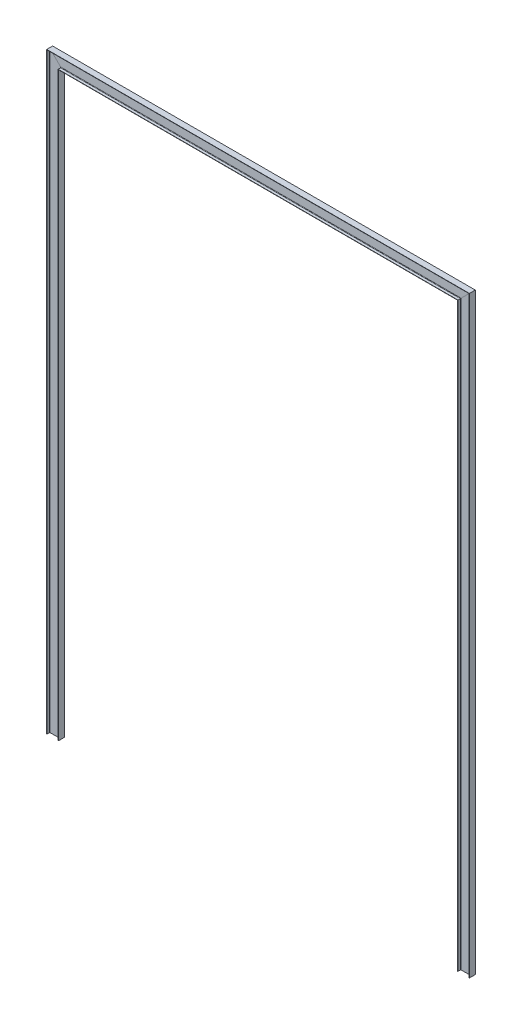
SolidWorks part; units mm, degrees
material "ASTM A36 Steel"
ref_plane "Front Plane" through (0, 0, 0) normal (0, 0, 1) x (1, 0, 0)
ref_plane "Top Plane" through (0, 0, 0) normal (0, 1, 0) x (1, 0, 0)
ref_plane "Right Plane" through (0, 0, 0) normal (1, 0, 0) x (0, 0, -1)
sketch "Sketch1" plane through (0, 0, 0) normal (0, 0, 1) x (1, 0, 0)
  line L0 (0, 0) -> (0, 10000)
  line L1 (0, 10000) -> (7000, 10000)
  line L2 (7000, 10000) -> (7000, 0)
  dimension "D1" = 10000
  dimension "D2" = 7000
other "W section W8X10(1)"
ref_plane "Plane1" through (0, 0, 0) normal (0, 1, 0) x (0, 0, 1)
sketch "Sketch11" plane through (0, 0, 0) normal (0, 1, 0) x (0, 0, 1)
  line L0 (-50.038, -100.203) -> (-50.038, -94.996)
  line L1 (-50.038, -94.996) -> (-9.779, -94.996)
  line L2 (-2.159, -87.376) -> (-2.159, 87.376)
  line L3 (-9.779, 94.996) -> (-50.038, 94.996)
  line L4 (-50.038, 94.996) -> (-50.038, 100.203)
  line L5 (-50.038, 100.203) -> (50.038, 100.203)
  line L6 (50.038, 100.203) -> (50.038, 94.996)
  line L7 (50.038, 94.996) -> (9.779, 94.996)
  line L8 (2.159, 87.376) -> (2.159, -87.376)
  line L9 (9.779, -94.996) -> (50.038, -94.996)
  line L10 (50.038, -94.996) -> (50.038, -100.203)
  line L11 (50.038, -100.203) -> (-50.038, -100.203)
  line L12 (0, 0) -> (0, 100.203) construction
  line L13 (-2.159, 0) -> (2.159, 0) construction
  arc A0 (-9.779, -94.996) -> (-2.159, -87.376) centre (-9.779, -87.376) ccw
  arc A1 (-2.159, 87.376) -> (-9.779, 94.996) centre (-9.779, 87.376) ccw
  arc A2 (9.779, 94.996) -> (2.159, 87.376) centre (9.779, 87.376) ccw
  arc A3 (2.159, -87.376) -> (9.779, -94.996) centre (9.779, -87.376) ccw
  point P23 (-50.038, 0)
  point P26 (0, -100.203)
  point P27 (50.038, 0)
  point P28 (0, 0)
  dimension "Ri" = 7.62
  dimension "D1" = 2.159
  dimension "D2" = 5.207
  dimension "Tw" = 4.318
  dimension "Bf" = 100.076
  dimension "Depth" = 200.406
  dimension "Tf" = 5.207
